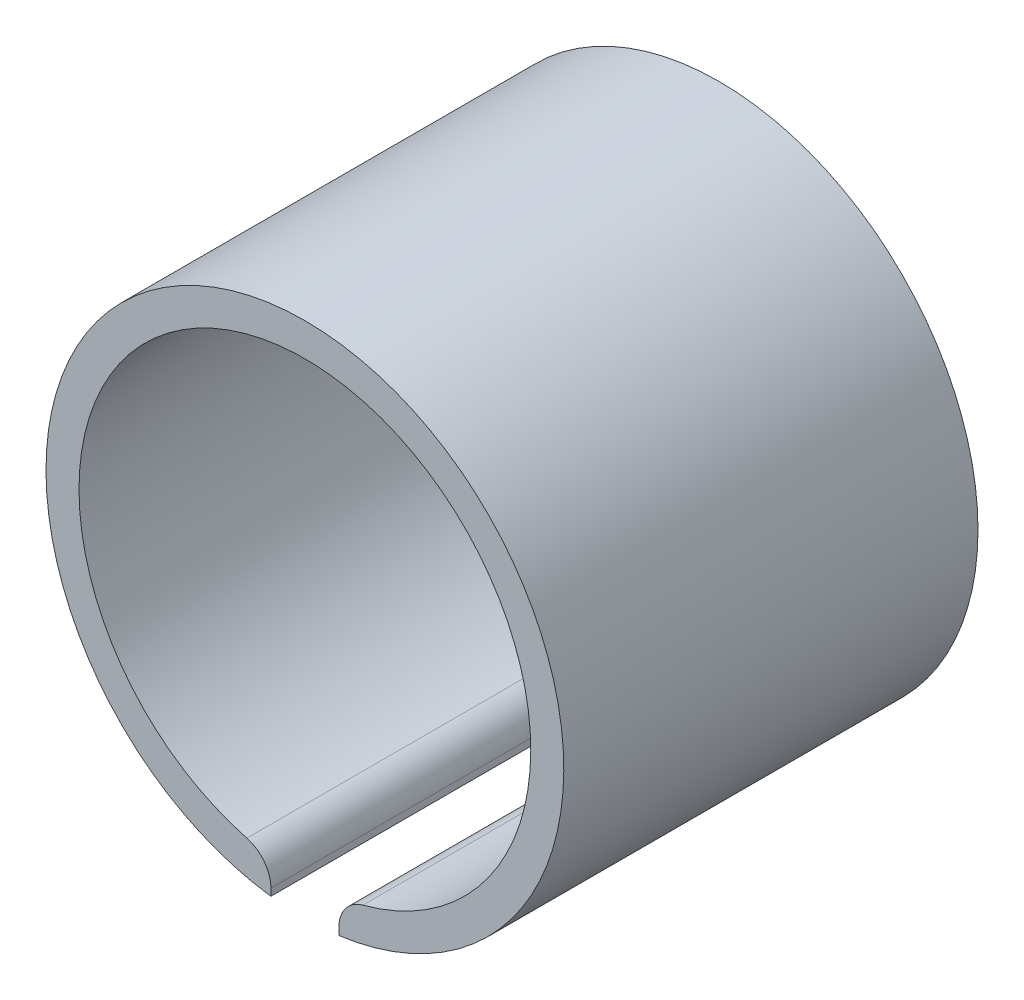
SolidWorks part; units mm, degrees
ref_plane "Front Plane" through (0, 0, 0) normal (0, 0, 1) x (1, 0, 0)
ref_plane "Top Plane" through (0, 0, 0) normal (0, 1, 0) x (1, 0, 0)
ref_plane "Right Plane" through (0, 0, 0) normal (1, 0, 0) x (0, 0, -1)
sketch "Sketch1" plane through (0, 0, 0) normal (0, 0, 1) x (1, 0, 0)
  circle A0 centre (0, 0) radius 20
  circle A1 centre (0, 0) radius 5
  dimension "D1" = 10
  dimension "D2" = 40
extrude "Boss-Extrude1" add sketch "Sketch1" along normal blind 2
sketch "Sketch2" plane through (0, 0, 2) normal (0, 0, 1) x (1, 0, 0)
  line L1 (-2.625, -14.9) -> (2.625, -14.9)
  line L2 (-2.625, -14.9) -> (-2.625, -20)
  line L3 (-2.625, -20) -> (2.625, -20)
  line L4 (2.625, -14.9) -> (2.625, -20)
  line L5 (-2.625, -14.9) -> (2.625, -20) construction
  line L6 (-2.625, -20) -> (2.625, -14.9) construction
  circle A0 centre (0, 0) radius 20
  circle A1 centre (0, 0) radius 17.45
  circle A2 centre (0, 0) radius 20 construction
  point P6 (0, -17.45)
  circle M3 centre (0, 0) radius 20
  dimension "D1" = 34.9
  dimension "D2" = 5.25
extrude "Boss-Extrude2" add sketch "Sketch2" along normal blind 30 contours A1 L4 L2 M3
fillet "Fillet1" radius 2.5 2 edges at (2.625, -17.2514, 17) (-2.625, -17.2514, 17)
